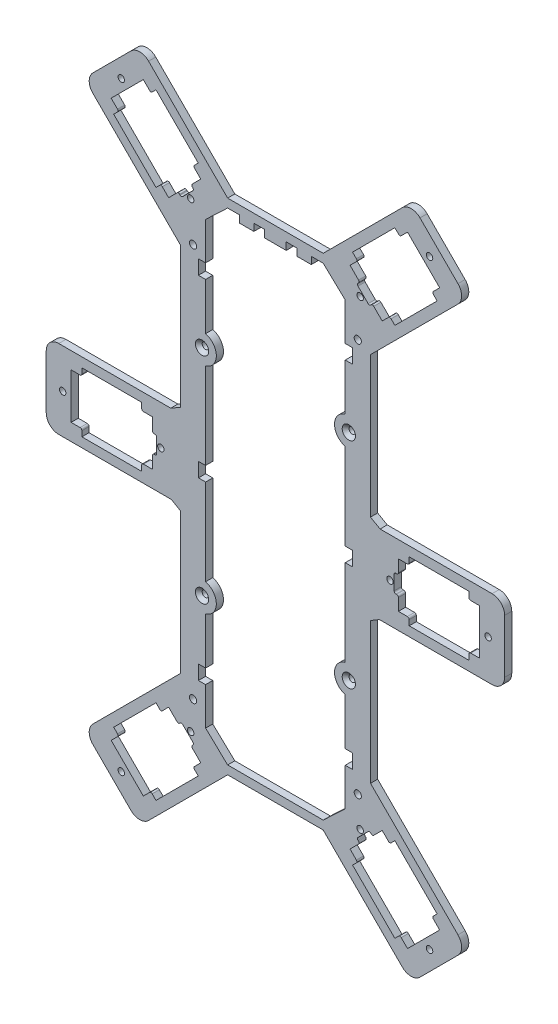
SolidWorks part; units mm, degrees
ref_plane "前视基准面" through (0, 0, 0) normal (0, 0, 1) x (1, 0, 0)
ref_plane "上视基准面" through (0, 0, 0) normal (0, 1, 0) x (1, 0, 0)
ref_plane "右视基准面" through (0, 0, 0) normal (1, 0, 0) x (0, 0, -1)
sketch "草图1" plane through (0, 0, 0) normal (0, 0, 1) x (1, 0, 0)
  line L0 (-33.1527, 2) -> (-33.1527, -2)
  line L1 (-33.6527, -2.5) -> (-33.8527, -2.5)
  line L2 (-34.3527, -3) -> (-34.3527, -6.35)
  line L3 (-34.3527, -6.35) -> (-36.8527, -6.35)
  line L4 (-37.3527, -6.85) -> (-37.3527, -8.35)
  line L5 (-37.3527, -8.35) -> (-54.0527, -8.35)
  line L6 (-54.0527, -8.35) -> (-54.0527, -6.85)
  line L7 (-26.5563, 51.8432) -> (-26.5563, 12.5444)
  line L8 (-53.4515, 78.7384) -> (-26.5563, 51.8432)
  line L9 (-32.2945, 63.3742) -> (-33.3551, 62.3135)
  line L10 (-33.3551, 62.3135) -> (-45.1638, 74.1222)
  line L11 (-27.4508, 63.9752) -> (-29.8196, 61.6064)
  line L12 (-29.8196, 61.6064) -> (-31.5874, 63.3742)
  line L13 (-23.6678, 64.4348) -> (-43.0425, 83.8095) construction
  line L14 (-33.3551, 85.9309) -> (-21.5465, 74.1222)
  line L15 (-13.3431, 69.7427) -> (-37.8952, 94.2947)
  line L16 (13.3431, 69.7427) -> (-13.3431, 69.7427)
  line L17 (-54.5527, -6.35) -> (-57.0527, -6.35)
  line L18 (-57.0527, -6.35) -> (-57.0527, 6.35)
  line L19 (-57.0527, 6.35) -> (-54.5527, 6.35)
  line L20 (-54.0527, 6.85) -> (-54.0527, 8.35)
  line L21 (-54.0527, 8.35) -> (-37.3527, 8.35)
  line L22 (-37.3527, 8.35) -> (-37.3527, 6.85)
  line L23 (-36.8527, 6.35) -> (-34.3527, 6.35)
  line L24 (-34.3527, 6.35) -> (-34.3527, 3)
  line L25 (26.5563, 12.5444) -> (26.5563, 51.8432)
  line L26 (29.2297, 11) -> (26.5563, 12.5444)
  line L27 (29.2297, 11) -> (64.0054, 11)
  line L28 (64.0054, 11) -> (64.0054, -11)
  line L29 (64.0054, -11) -> (29.0331, -11)
  line L30 (0, 0) -> (64.0054, 0) construction
  line L31 (-33.8527, 2.5) -> (-33.6527, 2.5)
  line L32 (26.5563, -12.4665) -> (29.0331, -11)
  line L33 (26.5563, -51.8432) -> (26.5563, -12.4665)
  line L34 (23.6678, -64.4348) -> (43.0425, -83.8095) construction
  line L35 (-23.6678, -64.4348) -> (-43.0425, -83.8095) construction
  line L36 (-23.2082, -67.5107) -> (-23.0667, -67.3693)
  line L37 (-22.6071, -72.3544) -> (-20.8394, -70.5866)
  line L38 (-45.8709, -77.6577) -> (-36.8907, -86.638)
  line L39 (-20.8394, -70.5866) -> (-23.2082, -68.2178)
  line L40 (-44.1032, -75.8899) -> (-45.8709, -77.6577)
  line L41 (33.3551, -85.9309) -> (21.5465, -74.1222)
  line L42 (53.4515, -78.7384) -> (26.5563, -51.8432)
  line L43 (13.3431, -69.7427) -> (37.8952, -94.2947)
  line L44 (36.8907, -86.638) -> (35.1229, -84.8702)
  line L45 (21.5465, -74.1222) -> (22.6071, -73.0615)
  line L46 (23.0667, -66.6622) -> (25.8952, -63.8338)
  line L47 (32.2945, -63.3742) -> (33.3551, -62.3135)
  line L48 (37.8952, -94.2947) -> (53.4515, -78.7384)
  line L49 (26.6023, -63.8338) -> (26.7437, -63.9752)
  line L50 (45.1638, -74.1222) -> (44.1032, -75.1828)
  line L51 (-26.5563, -12.4665) -> (-26.5563, -51.8432)
  line L52 (33.3551, -62.3135) -> (45.1638, -74.1222)
  line L53 (34.4158, -84.8702) -> (33.3551, -85.9309)
  line L54 (44.1032, -75.8899) -> (45.8709, -77.6577)
  line L55 (20.8394, -70.5866) -> (23.2082, -68.2178)
  line L56 (27.4508, -63.9752) -> (29.8196, -61.6064)
  line L57 (45.8709, -77.6577) -> (36.8907, -86.638)
  line L58 (22.6071, -72.3544) -> (20.8394, -70.5866)
  line L59 (29.8196, -61.6064) -> (31.5874, -63.3742)
  line L60 (23.2082, -67.5107) -> (23.0667, -67.3693)
  line L61 (-34.4158, -84.8702) -> (-33.3551, -85.9309)
  line L62 (-45.1638, -74.1222) -> (-44.1032, -75.1828)
  line L63 (-26.6023, -63.8338) -> (-26.7437, -63.9752)
  line L64 (-37.8952, -94.2947) -> (-53.4515, -78.7384)
  line L65 (-23.0667, -66.6622) -> (-25.8952, -63.8338)
  line L66 (-21.5465, -74.1222) -> (-22.6071, -73.0615)
  line L67 (-36.8907, -86.638) -> (-35.1229, -84.8702)
  line L68 (-13.3432, -67.3431) -> (13.3432, -67.3431)
  line L69 (-19.5, -61.5162) -> (-13.3432, -67.3431)
  line L70 (13.3432, -67.3431) -> (19.5, -61.5162)
  line L71 (19.5, -2) -> (19.5, -26.127)
  line L72 (19.5, 2) -> (21.5, 2)
  line L73 (21.5, -2) -> (19.5, -2)
  line L74 (-21.5, -51) -> (-21.5, -47)
  line L75 (-19.5, -47) -> (-19.5, -33.873)
  line L76 (-19.5, -2) -> (-21.5, -2)
  line L77 (-21.5, 2) -> (-21.5, -2)
  line L78 (-21.5, 2) -> (-19.5, 2)
  line L79 (-19.5, 2) -> (-19.5, 26.127)
  line L80 (-19.5, 47) -> (-21.5, 47)
  line L81 (-21.5, 51) -> (-21.5, 47)
  line L82 (-21.5, 51) -> (-19.5, 51)
  line L83 (-19.5, 51) -> (-19.5, 61.5162)
  line L84 (19.5, 47) -> (19.5, 33.873)
  line L85 (21.5, 47) -> (19.5, 47)
  line L86 (21.5, 51) -> (21.5, 47)
  line L87 (19.5, 51) -> (21.5, 51)
  line L88 (19.5, 61.5162) -> (19.5, 51)
  line L89 (13.3432, 67.3431) -> (19.5, 61.5162)
  line L90 (-19.5, 61.5162) -> (-13.3432, 67.3431)
  line L91 (-13.3432, 67.3431) -> (-10.015, 67.3431)
  line L92 (0, 67.3431) -> (0, -67.3431) construction
  line L93 (23.6678, 64.4348) -> (43.0425, 83.8095) construction
  line L94 (-36.8907, 86.638) -> (-35.1229, 84.8702)
  line L95 (-21.5465, 74.1222) -> (-22.6071, 73.0615)
  line L96 (-23.0667, 66.6622) -> (-25.8952, 63.8338)
  line L97 (-37.8952, 94.2947) -> (-53.4515, 78.7384)
  line L98 (-26.6023, 63.8338) -> (-26.7437, 63.9752)
  line L99 (-45.1638, 74.1222) -> (-44.1032, 75.1828)
  line L100 (-34.4158, 84.8702) -> (-33.3551, 85.9309)
  line L101 (-26.5563, -12.4665) -> (-29.0331, -11)
  line L102 (-64.0054, -11) -> (-29.0331, -11)
  line L103 (-64.0054, 11) -> (-64.0054, -11)
  line L104 (-29.2297, 11) -> (-64.0054, 11)
  line L105 (-29.2297, 11) -> (-26.5563, 12.5444)
  line L106 (23.2082, 67.5107) -> (23.0667, 67.3693)
  line L107 (29.8196, 61.6064) -> (31.5874, 63.3742)
  line L108 (22.6071, 72.3544) -> (20.8394, 70.5866)
  line L109 (33.8527, 2.5) -> (33.6527, 2.5)
  line L110 (34.3527, 6.35) -> (34.3527, 3)
  line L111 (36.8527, 6.35) -> (34.3527, 6.35)
  line L112 (37.3527, 8.35) -> (37.3527, 6.85)
  line L113 (54.0527, 8.35) -> (37.3527, 8.35)
  line L114 (54.0527, 6.85) -> (54.0527, 8.35)
  line L115 (57.0527, 6.35) -> (54.5527, 6.35)
  line L116 (57.0527, -6.35) -> (57.0527, 6.35)
  line L117 (54.5527, -6.35) -> (57.0527, -6.35)
  line L118 (54.0527, -8.35) -> (54.0527, -6.85)
  line L119 (37.3527, -8.35) -> (54.0527, -8.35)
  line L120 (37.3527, -6.85) -> (37.3527, -8.35)
  line L121 (34.3527, -6.35) -> (36.8527, -6.35)
  line L122 (34.3527, -3) -> (34.3527, -6.35)
  line L123 (33.6527, -2.5) -> (33.8527, -2.5)
  line L124 (33.1527, 2) -> (33.1527, -2)
  line L125 (45.8709, 77.6577) -> (36.8907, 86.638)
  line L126 (27.4508, 63.9752) -> (29.8196, 61.6064)
  line L127 (20.8394, 70.5866) -> (23.2082, 68.2178)
  line L128 (44.1032, 75.8899) -> (45.8709, 77.6577)
  line L129 (34.4158, 84.8702) -> (33.3551, 85.9309)
  line L130 (33.3551, 62.3135) -> (45.1638, 74.1222)
  line L131 (45.1638, 74.1222) -> (44.1032, 75.1828)
  line L132 (26.6023, 63.8338) -> (26.7437, 63.9752)
  line L133 (37.8952, 94.2947) -> (53.4515, 78.7384)
  line L134 (32.2945, 63.3742) -> (33.3551, 62.3135)
  line L135 (23.0667, 66.6622) -> (25.8952, 63.8338)
  line L136 (21.5465, 74.1222) -> (22.6071, 73.0615)
  line L137 (36.8907, 86.638) -> (35.1229, 84.8702)
  line L138 (13.3431, 69.7427) -> (37.8952, 94.2947)
  line L139 (53.4515, 78.7384) -> (26.5563, 51.8432)
  line L140 (33.3551, 85.9309) -> (21.5465, 74.1222)
  line L141 (-44.1032, 75.8899) -> (-45.8709, 77.6577)
  line L142 (-20.8394, 70.5866) -> (-23.2082, 68.2178)
  line L143 (-45.8709, 77.6577) -> (-36.8907, 86.638)
  line L144 (-22.6071, 72.3544) -> (-20.8394, 70.5866)
  line L145 (-23.2082, 67.5107) -> (-23.0667, 67.3693)
  line L146 (19.5, -61.5162) -> (19.5, -51)
  line L147 (19.5, -51) -> (21.5, -51)
  line L148 (21.5, 2) -> (21.5, -2)
  line L149 (21.5, -47) -> (19.5, -47)
  line L150 (-19.5, -51) -> (-19.5, -61.5162)
  line L151 (-21.5, -51) -> (-19.5, -51)
  line L152 (21.5, -47) -> (21.5, -51)
  line L153 (-19.5, -47) -> (-21.5, -47)
  line L154 (13.3431, -69.7427) -> (-13.3431, -69.7427)
  line L155 (-13.3431, -69.7427) -> (-37.8952, -94.2947)
  line L156 (-33.3551, -85.9309) -> (-21.5465, -74.1222)
  line L157 (-29.8196, -61.6064) -> (-31.5874, -63.3742)
  line L158 (-27.4508, -63.9752) -> (-29.8196, -61.6064)
  line L159 (-33.3551, -62.3135) -> (-45.1638, -74.1222)
  line L160 (-32.2945, -63.3742) -> (-33.3551, -62.3135)
  line L161 (-53.4515, -78.7384) -> (-26.5563, -51.8432)
  line L162 (-10.015, 67.3431) -> (-10.015, 65.3431)
  line L163 (-10.015, 65.3431) -> (-6.015, 65.3431)
  line L164 (-6.015, 65.3431) -> (-6.015, 67.3431)
  line L165 (-6.015, 67.3431) -> (-3.015, 67.3431)
  line L166 (-3.015, 67.3431) -> (-3.015, 65.267)
  line L167 (-3.015, 65.267) -> (3.015, 65.267)
  line L168 (3.015, 67.3431) -> (3.015, 65.267)
  line L169 (10.015, 67.3431) -> (13.3432, 67.3431)
  line L170 (6.015, 67.3431) -> (3.015, 67.3431)
  line L171 (6.015, 65.3431) -> (6.015, 67.3431)
  line L172 (10.015, 65.3431) -> (6.015, 65.3431)
  line L173 (10.015, 67.3431) -> (10.015, 65.3431)
  line L174 (19.5, -33.873) -> (19.5, -47)
  line L175 (-19.5, -26.127) -> (-19.5, -2)
  line L176 (19.5, 26.127) -> (19.5, 2)
  line L177 (-19.5, 33.873) -> (-19.5, 47)
  arc A0 (-33.1527, -2) -> (-33.6527, -2.5) centre (-33.6527, -2) cw
  arc A1 (-34.3527, -3) -> (-33.8527, -2.5) centre (-33.8527, -3) cw
  arc A2 (-37.3527, -6.85) -> (-36.8527, -6.35) centre (-36.8527, -6.85) cw
  arc A3 (-54.5527, -6.35) -> (-54.0527, -6.85) centre (-54.5527, -6.85) cw
  arc A4 (-34.4158, 84.8702) -> (-35.1229, 84.8702) centre (-34.7694, 85.2238) cw
  arc A5 (-22.6071, 72.3544) -> (-22.6071, 73.0615) centre (-22.2536, 72.708) cw
  arc A6 (-54.0527, 6.85) -> (-54.5527, 6.35) centre (-54.5527, 6.85) cw
  arc A7 (-36.8527, 6.35) -> (-37.3527, 6.85) centre (-36.8527, 6.85) cw
  circle A8 centre (32.0027, 0) radius 0.9
  circle A9 centre (59.4027, 0) radius 0.9
  arc A10 (-23.0667, -67.3693) -> (-23.0667, -66.6622) centre (-23.4203, -67.0158) ccw
  arc A11 (-44.1032, -75.8899) -> (-44.1032, -75.1828) centre (-44.4567, -75.5364) ccw
  arc A12 (34.4158, -84.8702) -> (35.1229, -84.8702) centre (34.7694, -85.2238) cw
  arc A13 (22.6071, -72.3544) -> (22.6071, -73.0615) centre (22.2536, -72.708) cw
  arc A14 (-33.8527, 2.5) -> (-34.3527, 3) centre (-33.8527, 3) cw
  arc A15 (33.6527, 2.5) -> (33.1527, 2) centre (33.6527, 2) ccw
  arc A16 (23.2082, -67.5107) -> (23.2082, -68.2178) centre (22.8546, -67.8643) cw
  circle A17 centre (43.0425, -83.8095) radius 0.9
  arc A18 (25.8952, -63.8338) -> (26.6023, -63.8338) centre (26.2487, -64.1873) cw
  circle A19 centre (23.6678, -64.4348) radius 0.9
  arc A20 (27.4508, -63.9752) -> (26.7437, -63.9752) centre (27.0973, -63.6216) cw
  arc A21 (32.2945, -63.3742) -> (31.5874, -63.3742) centre (31.9409, -63.0206) cw
  arc A22 (44.1032, -75.8899) -> (44.1032, -75.1828) centre (44.4567, -75.5364) cw
  arc A23 (23.0667, -67.3693) -> (23.0667, -66.6622) centre (23.4203, -67.0158) cw
  arc A24 (-32.2945, -63.3742) -> (-31.5874, -63.3742) centre (-31.9409, -63.0206) ccw
  arc A25 (-27.4508, -63.9752) -> (-26.7437, -63.9752) centre (-27.0973, -63.6216) ccw
  circle A26 centre (-23.6678, -64.4348) radius 0.9
  circle A27 centre (-20.5, -30) radius 0.8
  circle A28 centre (20.5, -30) radius 0.8
  arc A29 (-19.5, 26.127) -> (-19.5, 33.873) centre (-20.5, 30) ccw
  arc A30 (-19.5, -33.873) -> (-19.5, -26.127) centre (-20.5, -30) ccw
  arc A31 (19.5, -26.127) -> (19.5, -33.873) centre (20.5, -30) ccw
  arc A32 (19.5, 33.873) -> (19.5, 26.127) centre (20.5, 30) ccw
  circle A33 centre (-20.5, 30) radius 0.8
  circle A34 centre (20.5, 30) radius 0.8
  circle A35 centre (-23, 53.6665) radius 1
  circle A36 centre (23, 53.6665) radius 1
  circle A37 centre (-23, -56.2676) radius 1
  circle A38 centre (23, -56.2676) radius 1
  arc A39 (-23.2082, 67.5107) -> (-23.2082, 68.2178) centre (-22.8546, 67.8643) cw
  circle A40 centre (-43.0425, 83.8095) radius 0.9
  arc A41 (33.8527, 2.5) -> (34.3527, 3) centre (33.8527, 3) ccw
  arc A42 (36.8527, 6.35) -> (37.3527, 6.85) centre (36.8527, 6.85) ccw
  arc A43 (54.0527, 6.85) -> (54.5527, 6.35) centre (54.5527, 6.85) ccw
  arc A44 (54.5527, -6.35) -> (54.0527, -6.85) centre (54.5527, -6.85) ccw
  arc A45 (37.3527, -6.85) -> (36.8527, -6.35) centre (36.8527, -6.85) ccw
  arc A46 (34.3527, -3) -> (33.8527, -2.5) centre (33.8527, -3) ccw
  arc A47 (33.1527, -2) -> (33.6527, -2.5) centre (33.6527, -2) ccw
  arc A48 (-33.6527, 2.5) -> (-33.1527, 2) centre (-33.6527, 2) cw
  circle A49 centre (-59.4027, 0) radius 0.9
  circle A50 centre (-32.0027, 0) radius 0.9
  arc A51 (-25.8952, 63.8338) -> (-26.6023, 63.8338) centre (-26.2487, 64.1873) cw
  circle A52 centre (-23.6678, 64.4348) radius 0.9
  arc A53 (-27.4508, 63.9752) -> (-26.7437, 63.9752) centre (-27.0973, 63.6216) cw
  arc A54 (-32.2945, 63.3742) -> (-31.5874, 63.3742) centre (-31.9409, 63.0206) cw
  arc A55 (23.0667, 67.3693) -> (23.0667, 66.6622) centre (23.4203, 67.0158) ccw
  arc A56 (44.1032, 75.8899) -> (44.1032, 75.1828) centre (44.4567, 75.5364) ccw
  arc A57 (32.2945, 63.3742) -> (31.5874, 63.3742) centre (31.9409, 63.0206) ccw
  arc A58 (27.4508, 63.9752) -> (26.7437, 63.9752) centre (27.0973, 63.6216) ccw
  circle A59 centre (23.6678, 64.4348) radius 0.9
  arc A60 (25.8952, 63.8338) -> (26.6023, 63.8338) centre (26.2487, 64.1873) ccw
  circle A61 centre (43.0425, 83.8095) radius 0.9
  arc A62 (23.2082, 67.5107) -> (23.2082, 68.2178) centre (22.8546, 67.8643) ccw
  arc A63 (22.6071, 72.3544) -> (22.6071, 73.0615) centre (22.2536, 72.708) ccw
  arc A64 (34.4158, 84.8702) -> (35.1229, 84.8702) centre (34.7694, 85.2238) ccw
  arc A65 (-44.1032, 75.8899) -> (-44.1032, 75.1828) centre (-44.4567, 75.5364) cw
  arc A66 (-23.0667, 67.3693) -> (-23.0667, 66.6622) centre (-23.4203, 67.0158) cw
  arc A67 (-25.8952, -63.8338) -> (-26.6023, -63.8338) centre (-26.2487, -64.1873) ccw
  circle A68 centre (-43.0425, -83.8095) radius 0.9
  arc A69 (-23.2082, -67.5107) -> (-23.2082, -68.2178) centre (-22.8546, -67.8643) ccw
  arc A74 (-22.6071, -72.3544) -> (-22.6071, -73.0615) centre (-22.2536, -72.708) ccw
  arc A75 (-34.4158, -84.8702) -> (-35.1229, -84.8702) centre (-34.7694, -85.2238) ccw
  point P325 (0, 65.267)
  dimension "D14" = 1.6
  dimension "D17" = 60
  dimension "D18" = 8
  dimension "D19" = 46
  dimension "D21" = 2
  dimension "D1" = 39
  dimension "D2" = 4
  dimension "D3" = 6.03
  dimension "D4" = 22
  dimension "D5" = 22
  dimension "D6" = 2
  dimension "D7" = 45
  dimension "D8" = 4
  dimension "D9" = 67.3431
  dimension "D10" = 4
  dimension "D11" = 3
  dimension "D12" = 47
  dimension "D13" = 43
  dimension "D15" = 1
  dimension "D16" = 1
  dimension "D20" = 23
  dimension "D22" = 46
  dimension "D23" = 23
extrude "凸台-拉伸1" add sketch "草图1" along normal blind 2
fillet "圆角1" radius 3.5 12 edges at (53.4515, -78.7384, 1) (37.8952, -94.2947, 1) (-37.8952, -94.2947, 1) (-53.4515, -78.7384, 1) (-64.0054, -11, 1) (-64.0054, 11, 1) (64.0054, -11, 1) (64.0054, 11, 1) (53.4515, 78.7384, 1) (37.8952, 94.2947, 1) (-53.4515, 78.7384, 1) (-37.8952, 94.2947, 1)
hole_wizard "打孔尺寸开槽半沉头螺钉的类型1" positions "草图2" profile "草图3" size "M1.6" standard "GB" slot yes
sketch "草图2" plane through (0, 0, 2) normal (0, 0, 1) x (1, 0, 0)
  point P0 (-20.5, 30)
  point P3 (20.5, 30)
  point P6 (-20.5, -30)
  point P9 (20.5, -30)
sketch "草图3" plane through (-20.5, 30, 2) normal (1, 0, 0) x (0, -1, 0)
  line L0 (0, 0) -> (0, 4.1908)
  line L1 (0, 4.1908) -> (0.9, 3.65)
  line L2 (0.9, 3.65) -> (0.9, 0.95)
  line L3 (0.9, 0.95) -> (1.85, 0)
  line L5 (1.85, 0) -> (0, 0)
  line L6 (-0.9, 0.95) -> (-1.85, 0) construction
  line L10 (0, 4.1908) -> (-0.9, 3.65) construction
  line L11 (0, -6.35) -> (0, 107.95) construction
  dimension "孔直径" = 1.8
  dimension "孔深度" = 3.65
  dimension "近端锥形沉头孔直径" = 3.7
  dimension "近端锥形沉头孔角度" = 90
  dimension "导头角度" = 118
